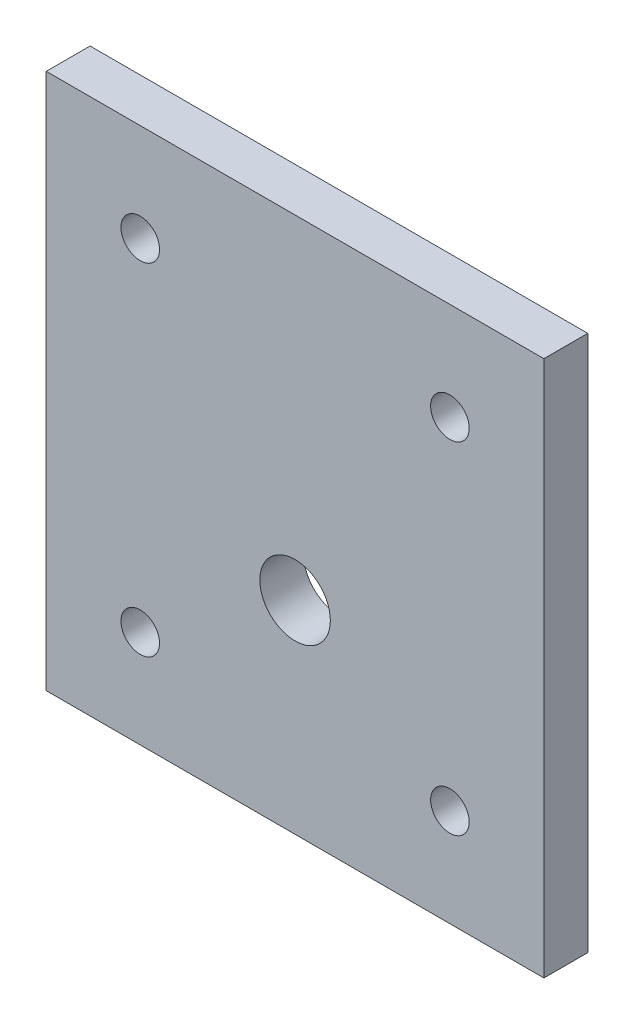
SolidWorks part; units mm, degrees
ref_plane "Front Plane" through (0, 0, 0) normal (0, 0, 1) x (1, 0, 0)
ref_plane "Top Plane" through (0, 0, 0) normal (0, 1, 0) x (1, 0, 0)
ref_plane "Right Plane" through (0, 0, 0) normal (1, 0, 0) x (0, 0, -1)
sketch "Sketch1" plane through (0, 0, 0) normal (0, 0, 1) x (1, 0, 0)
  line L0 (23.5034, -26.6844) -> (45.9189, -26.6844) construction
  line L1 (16.6987, 5.0709) -> (52.7236, 5.0709)
  line L2 (16.6987, 5.0709) -> (16.6987, -33.756)
  line L3 (16.6987, -33.756) -> (52.7236, -33.756)
  line L4 (52.7236, 5.0709) -> (52.7236, -33.756)
  line L5 (34.7111, -19.0791) -> (34.7111, -33.756) construction
  line L11 (45.9189, -26.6844) -> (45.9189, -2.0006) construction
  line L13 (45.9189, -14.3425) -> (52.7236, -14.3425) construction
  line L14 (34.7111, -19.0791) -> (45.9189, -19.0791) construction
  circle A1 centre (45.9189, -2.0006) radius 1.397
  circle A2 centre (23.5034, -2.0006) radius 1.397
  circle A3 centre (23.5034, -26.6844) radius 1.397
  circle A4 centre (45.9189, -26.6844) radius 1.397
  circle A5 centre (34.7111, -19.0791) radius 2.5527
extrude "Boss-Extrude1" add sketch "Sketch1" along normal blind 3.175
